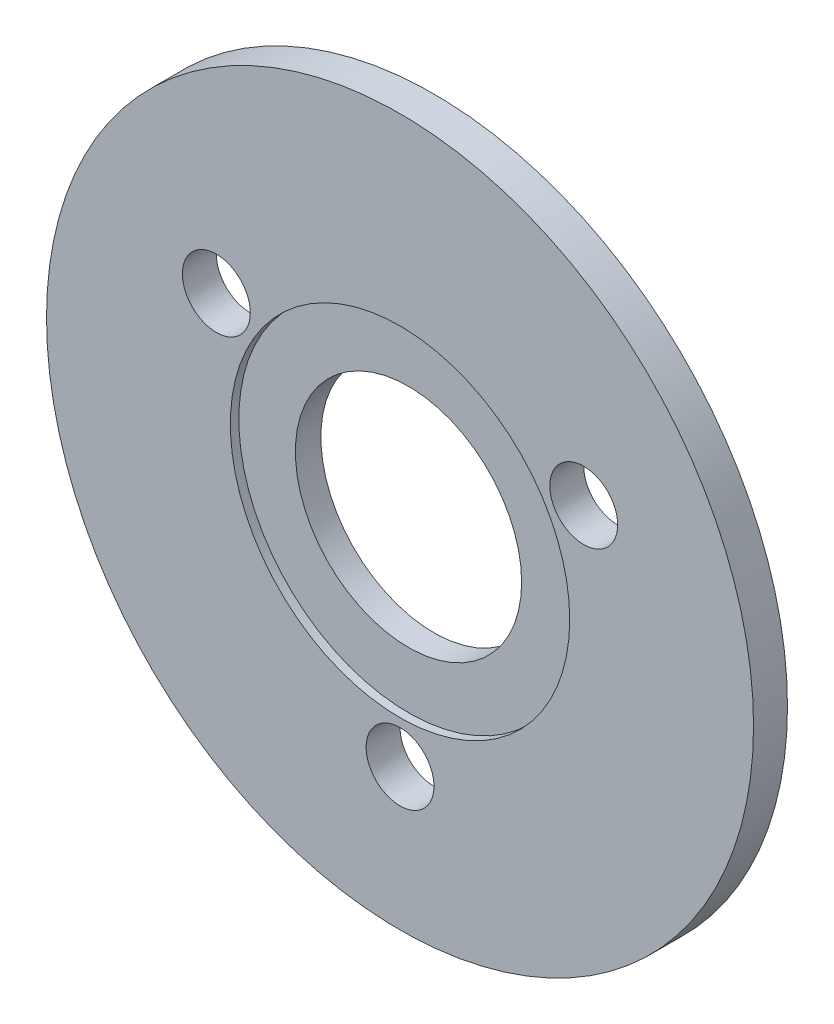
SolidWorks part; units mm, degrees
ref_plane "前视基准面" through (0, 0, 0) normal (0, 0, 1) x (1, 0, 0)
ref_plane "上视基准面" through (0, 0, 0) normal (0, 1, 0) x (1, 0, 0)
ref_plane "右视基准面" through (0, 0, 0) normal (1, 0, 0) x (0, 0, -1)
sketch "草图1" plane through (0, 0, 0) normal (0, 0, 1) x (1, 0, 0)
  line L0 (0, 0) -> (0, -7.5) construction
  circle A1 centre (0, 0) radius 12.5
  circle A2 centre (0, 0) radius 4
  circle A3 centre (0, -7.5) radius 1.2
  circle A4 centre (-6.4952, 3.75) radius 1.2
  circle A5 centre (6.4952, 3.75) radius 1.2
  point P17 (0, 0)
  dimension "D3" = 7.5
  dimension "D1" = 25
  dimension "D2" = 8
  dimension "D4" = 2.4
  dimension "D5" = 3
extrude "凸台-拉伸1" add sketch "草图1" along normal blind 1.2
sketch "草图3" plane through (0, 0, 1.2) normal (0, 0, 1) x (1, 0, 0)
  circle A2 centre (0, 0) radius 6
  point P1 (-1.7481, 0.8219)
  dimension "D1" = 12
extrude "切除-拉伸2" cut sketch "草图3" against normal blind 0.3
